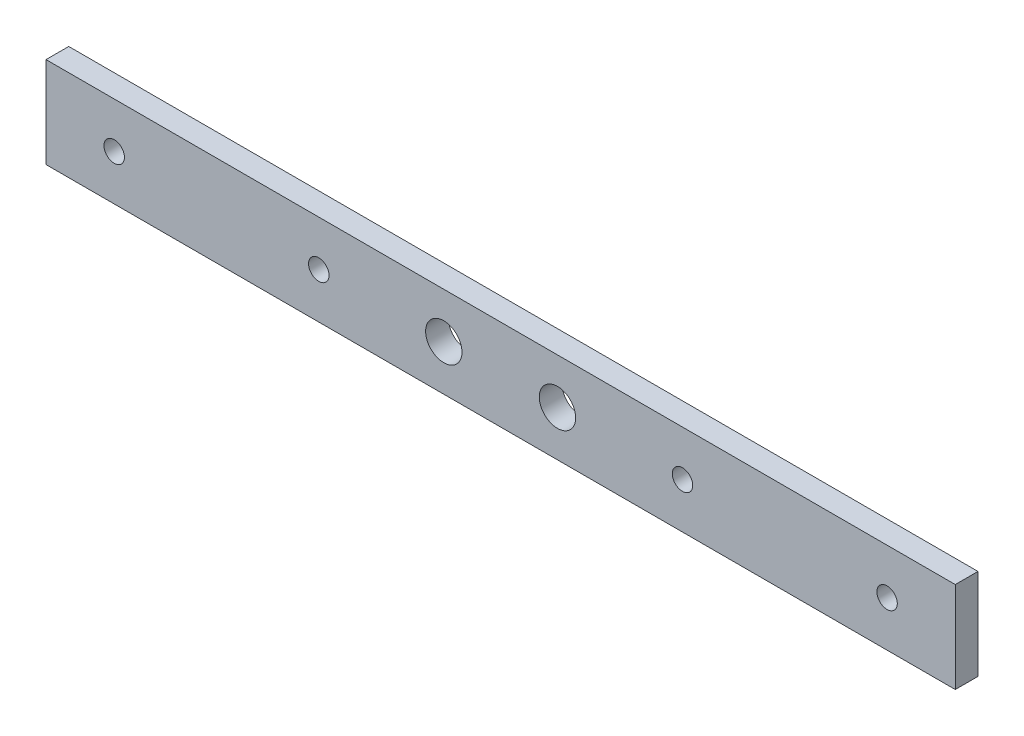
SolidWorks part; units mm, degrees
ref_plane "Plan de face" through (0, 0, 0) normal (0, 0, 1) x (1, 0, 0)
ref_plane "Plan de dessus" through (0, 0, 0) normal (0, 1, 0) x (1, 0, 0)
ref_plane "Plan de droite" through (0, 0, 0) normal (1, 0, 0) x (0, 0, -1)
sketch "Esquisse1" plane through (0, 0, 0) normal (0, 0, 1) x (1, 0, 0)
  line L0 (-100, 0) -> (100, 0) construction
  line L5 (-100, -10) -> (100, -10)
  line L6 (-100, -10) -> (-100, 10)
  line L7 (-100, 10) -> (100, 10)
  line L8 (100, -10) -> (100, 10)
  line L9 (-100, -10) -> (100, 10) construction
  line L10 (-100, 10) -> (100, -10) construction
  line L11 (0, -1000) -> (0, 49000) construction
  circle A6 centre (-85, 0) radius 2.25
  circle A7 centre (-40, 0) radius 2.25
  circle A8 centre (40, 0) radius 2.25
  circle A9 centre (85, 0) radius 2.25
  circle A10 centre (-12.5, 0) radius 4
  circle A11 centre (12.5, 0) radius 4
  point P0 (0, 0)
  dimension "D1" = 200
  dimension "D3" = 8
  dimension "D4" = 4.5
  dimension "D2" = 20
  dimension "D5" = 15
  dimension "D6" = 40
  dimension "D7" = 25
extrude "Boss.-Extru.1" add sketch "Esquisse1" along normal blind 5
